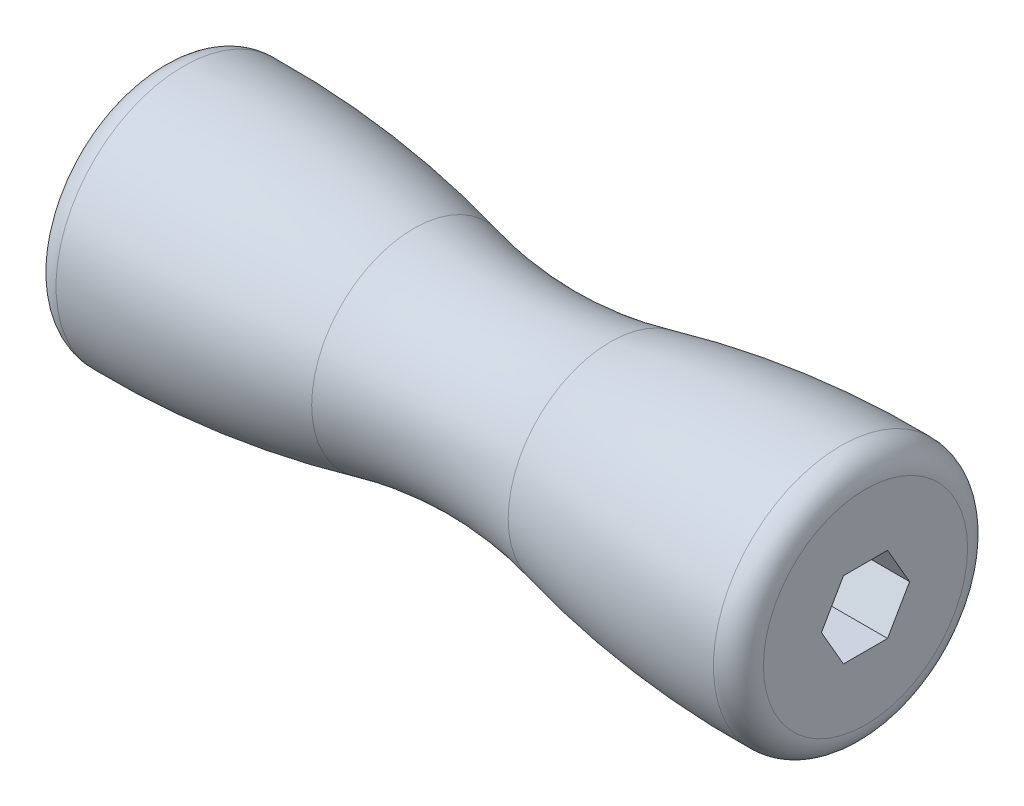
SolidWorks part; units mm, degrees
ref_plane "Front Plane" through (0, 0, 0) normal (0, 0, 1) x (1, 0, 0)
ref_plane "Top Plane" through (0, 0, 0) normal (0, 1, 0) x (1, 0, 0)
ref_plane "Right Plane" through (0, 0, 0) normal (1, 0, 0) x (0, 0, -1)
sketch "Sketch2" plane through (0, 0, 0) normal (0, 0, 1) x (1, 0, 0)
  line L0 (-30, 0) -> (30, 0) construction
  line L3 (-25, 0) -> (-25, 7.2181)
  line L4 (-6.9483, 7.2181) -> (6.9483, 7.2181) construction
  line L5 (0, 7.2181) -> (0, 0) construction
  line L6 (25, 7.2181) -> (25, 0)
  line L7 (25, 0) -> (-25, 0)
  line L8 (-25, 7.2181) -> (25, 7.2181) construction
  line L9 (23.2433, 9) -> (-23.2433, 9) construction
  arc A0 (-25, 7.2181) -> (-23.2433, 9) centre (-23.2179, 7.2181) cw
  arc A1 (-23.2433, 9) -> (-6.9483, 7.2181) centre (-22.2956, -57.7322) cw
  arc A2 (-6.9483, 7.2181) -> (6.9483, 7.2181) centre (0, 36.6237) ccw
  arc A3 (6.9483, 7.2181) -> (23.2433, 9) centre (22.2956, -57.7322) cw
  arc A4 (23.2433, 9) -> (25, 7.2181) centre (23.2179, 7.2181) cw
  dimension "D3" = 1.7821
  dimension "D1" = 50
  dimension "D2" = 9
revolve "Revolve1" add sketch "Sketch2" angle 360 about L7
sketch "Sketch3" plane through (25, 0, 0) normal (1, 0, 0) x (0, 0, -1)
  line L1 (3.1177, 0) -> (1.5588, 2.7)
  line L2 (1.5588, 2.7) -> (-1.5588, 2.7)
  line L3 (-1.5588, 2.7) -> (-3.1177, 0)
  line L4 (-3.1177, 0) -> (-1.5588, -2.7)
  line L5 (-1.5588, -2.7) -> (1.5588, -2.7)
  line L6 (1.5588, -2.7) -> (3.1177, 0)
  circle A1 centre (0, 0) radius 2.7 construction
  dimension "D1" = 5.4
extrude "Cut-Extrude1" cut sketch "Sketch3" against normal through all
